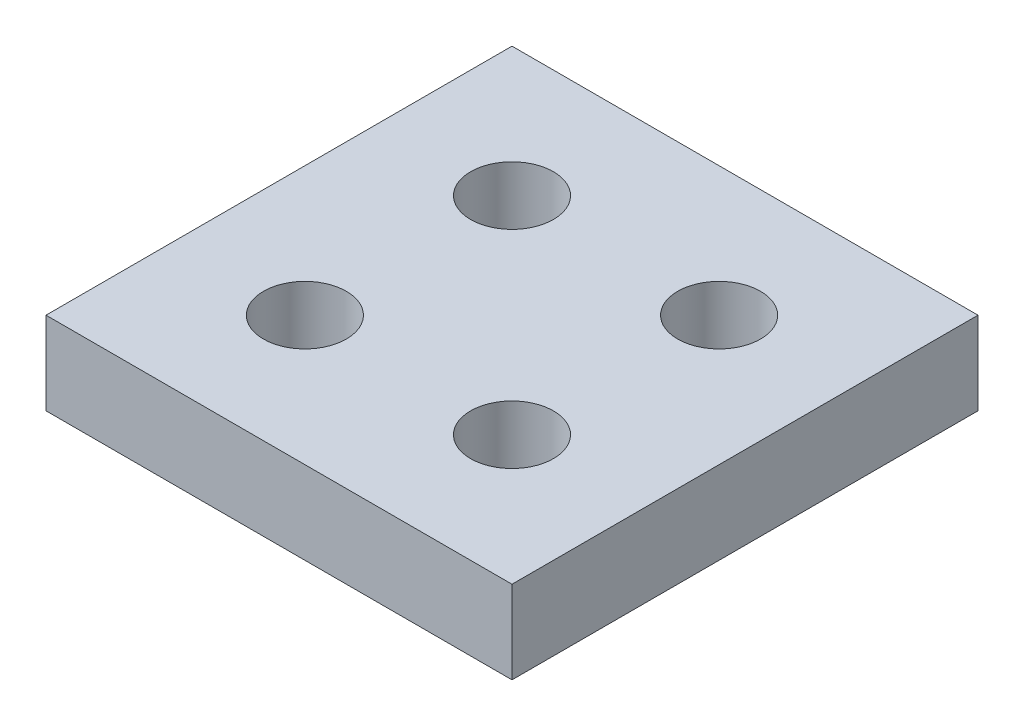
SolidWorks part; units mm, degrees
ref_plane "前视基准面" through (0, 0, 0) normal (0, 0, 1) x (1, 0, 0)
ref_plane "上视基准面" through (0, 0, 0) normal (0, 1, 0) x (1, 0, 0)
ref_plane "右视基准面" through (0, 0, 0) normal (1, 0, 0) x (0, 0, -1)
sketch "草图1" plane through (0, 0, 0) normal (0, 1, 0) x (1, 0, 0)
  line L1 (-2.25, -2.25) -> (2.25, -2.25)
  line L2 (-2.25, -2.25) -> (-2.25, 2.25)
  line L3 (-2.25, 2.25) -> (2.25, 2.25)
  line L4 (2.25, -2.25) -> (2.25, 2.25)
  line L5 (-2.25, -2.25) -> (2.25, 2.25) construction
  line L6 (-2.25, 2.25) -> (2.25, -2.25) construction
  circle A0 centre (-1, 1) radius 0.4
  circle A1 centre (1, 1) radius 0.4
  circle A2 centre (1, -1) radius 0.4
  circle A3 centre (-1, -1) radius 0.4
  point P0 (0, 0)
  point P17 (0, 0)
  dimension "D3" = 0.8
  dimension "D1" = 4.5
  dimension "D2" = 45
  dimension "D5" = 1
  dimension "D4" = 4
extrude "凸台-拉伸1" add sketch "草图1" along normal blind 0.8
